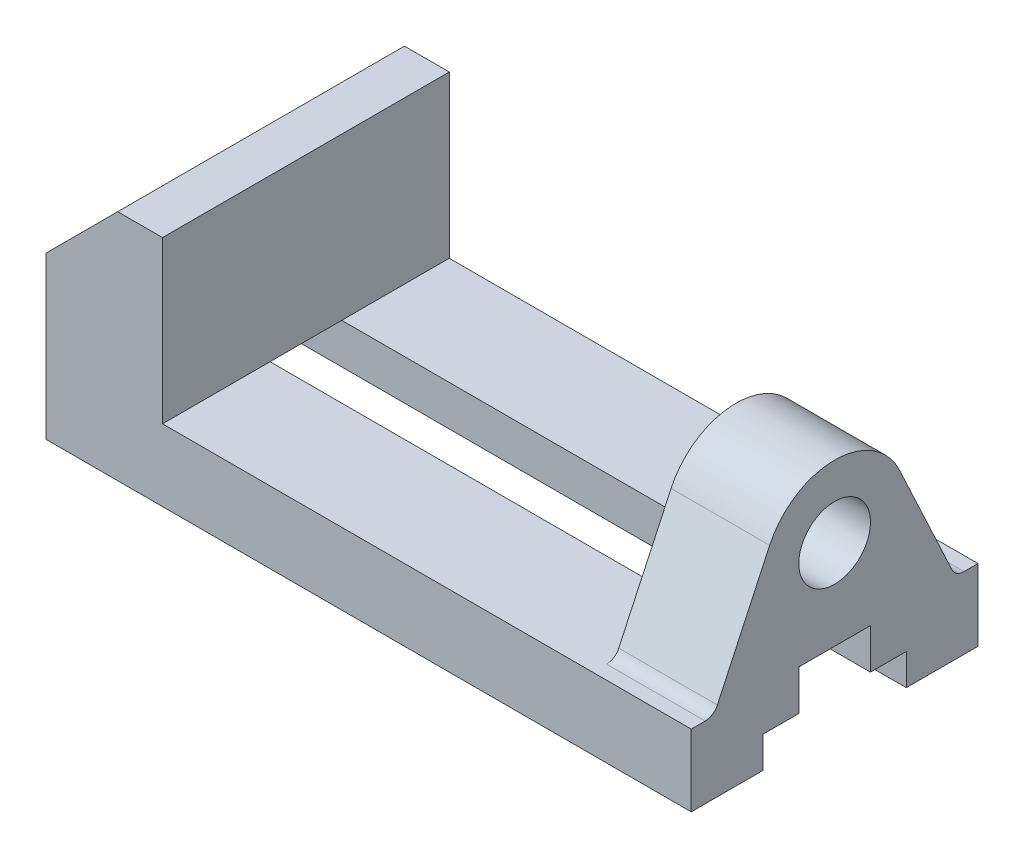
SolidWorks part; units mm, degrees
material "AISI 1020"
ref_plane "Front Plane" through (0, 0, 0) normal (0, 0, 1) x (1, 0, 0)
ref_plane "Top Plane" through (0, 0, 0) normal (0, 1, 0) x (1, 0, 0)
ref_plane "Right Plane" through (0, 0, 0) normal (1, 0, 0) x (0, 0, -1)
sketch "Sketch1" plane through (0, 0, 0) normal (0, 0, 1) x (1, 0, 0)
  line L0 (0, 0) -> (0, 36)
  line L1 (0, 36) -> (16, 52)
  line L2 (16, 52) -> (26, 52)
  line L3 (26, 52) -> (26, 16)
  line L4 (26, 16) -> (144, 16)
  line L5 (144, 16) -> (144, 0)
  line L6 (144, 0) -> (0, 0)
  dimension "D1" = 144
  dimension "D2" = 16
  dimension "D3" = 16
  dimension "D4" = 16
  dimension "D5" = 10
  dimension "D6" = 36
extrude "Boss-Extrude1" add sketch "Sketch1" along normal mid plane 64 contours L6 L0 L1 L2 L3 L4 L5
sketch "Sketch3" plane through (144, 0, 0) normal (1, 0, 0) x (0, 0, -1)
  line L0 (0, 0) -> (0, 57.51) construction
  line L1 (-32, 52) -> (32, 52) construction
  line L2 (-26.9802, 16) -> (-14.5009, 42.7619)
  line L3 (14.5009, 42.7619) -> (26.9802, 16)
  line L4 (26.9802, 16) -> (-26.9802, 16)
  line L5 (-32, 16) -> (32, 16) construction
  arc A0 (-14.5009, 42.7619) -> (14.5009, 42.7619) centre (0, 36) cw
  circle A1 centre (0, 36) radius 8
  dimension "D2" = 16
  dimension "D3" = 16
  dimension "D1" = 50
extrude "Boss-Extrude2" add sketch "Sketch3" against normal blind 22 contours L2 A0 L3 L4 | A1
fillet "Fillet1" radius 3 2 edges at (133, 16, 26.9802) (133, 16, -26.9802)
sketch "Sketch4" plane through (144, 0, 0) normal (1, 0, 0) x (0, 0, -1)
  line L0 (0, 0) -> (0, 38.4844) construction
  line L1 (-16, -4.4236) -> (-16, 7)
  line L2 (-16, 7) -> (-8, 7)
  line L3 (-8, 7) -> (-8, 16)
  line L4 (-8, 16) -> (8, 16)
  line L5 (8, 16) -> (8, 7)
  line L6 (8, 7) -> (16, 7)
  line L7 (16, 7) -> (16, -4.4236)
  line L8 (16, -4.4236) -> (-16, -4.4236)
  line L9 (-32, 0) -> (32, 0) construction
  dimension "D1" = 16
  dimension "D2" = 7
  dimension "D3" = 16
  dimension "D4" = 32
extrude "Cut-Extrude1" cut sketch "Sketch4" against normal through all
hole_wizard "Ø1.0mm Dowel Hole1" positions "Sketch5" profile "Sketch6" hole size "Ø1.0" standard "ANSI Metric"
sketch "Sketch5" plane through (0, 0, 0) normal (0, -1, 0) x (-1, 0, 0)
  line L0 (0, 16) -> (0, 32) construction
  line L1 (-144, 32) -> (0, 32) construction
  point P0 (-38, 22)
  dimension "D1" = 38
  dimension "D2" = 10
sketch "Sketch6" plane through (38, 0, -22) normal (1, 0, 0) x (0, 0, -1)
  line L0 (0, 0) -> (0, 11.7321)
  line L1 (0, 11.7321) -> (3, 10)
  line L2 (3, 10) -> (3, 0)
  line L5 (3, 0) -> (0, 0)
  line L10 (0, 11.7321) -> (-3, 10) construction
  line L11 (0, -6.35) -> (0, 107.95) construction
  dimension "Hole Dia." = 6
  dimension "Hole Depth" = 10
  dimension "Drill Angle" = 120
pattern_linear "LPattern1" count 2 spacing 70 along (1, 0, 0) count 2 spacing 44 along (0, 0, 1) of "Ø1.0mm Dowel Hole1"
